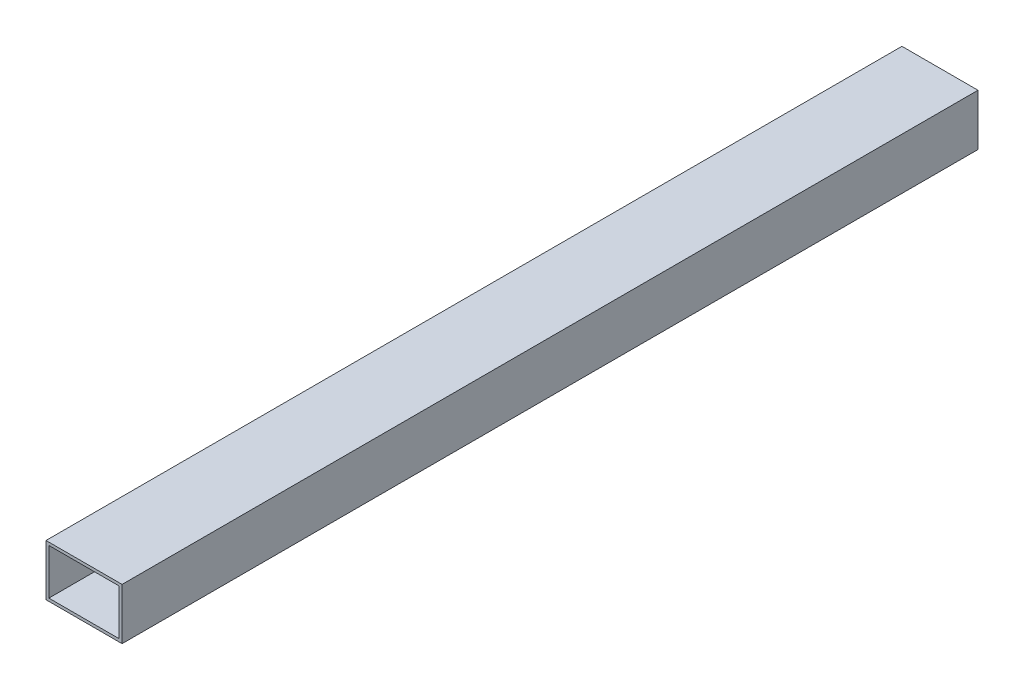
SolidWorks part; units mm, degrees
material "AISI 1020 Acier laminé à froid"
ref_plane "Plan de face" through (0, 0, 0) normal (0, 0, 1) x (1, 0, 0)
ref_plane "Plan de dessus" through (0, 0, 0) normal (0, 1, 0) x (1, 0, 0)
ref_plane "Plan de droite" through (0, 0, 0) normal (1, 0, 0) x (0, 0, -1)
sketch "Esquisse1" plane through (0, 0, 0) normal (0, 0, 1) x (1, 0, 0)
  line L1 (0, 0) -> (40, 0)
  line L2 (0, 0) -> (0, 27)
  line L3 (0, 27) -> (40, 27)
  line L4 (40, 0) -> (40, 27)
  line L5 (1.5, 25.5) -> (38.5, 25.5)
  line L6 (1.5, 25.5) -> (1.5, 1.5)
  line L7 (1.5, 1.5) -> (38.5, 1.5)
  line L8 (38.5, 25.5) -> (38.5, 1.5)
  dimension "D1" = 40
  dimension "D2" = 27
  dimension "D3" = 1.5
  dimension "D4" = 1.5
  dimension "D5" = 1.5
  dimension "D6" = 1.5
extrude "Boss.-Extru.1" add sketch "Esquisse1" along normal blind 450
sketch "Esquisse2" plane through (0, 0, 0) normal (0, 1, 0) x (1, 0, 0)
  line L0 (0, -450) -> (40, -410)
  line L1 (40, -450) -> (40, 0) construction
  line L2 (0, -450) -> (40, -450)
  line L3 (40, -450) -> (40, -410)
  dimension "D1" = 45
extrude "Enlèv. mat.-Extru.1" [suppressed] cut sketch "Esquisse2" along normal through all
sketch "Esquisse4" plane through (0, 0, 0) normal (0, 1, 0) x (1, 0, 0)
  line L0 (0, 0) -> (40, -40)
  line L1 (40, -450) -> (40, 0) construction
  line L2 (40, -40) -> (40, 0)
  line L3 (40, 0) -> (0, 0)
  dimension "D1" = 45
extrude "Enlèv. mat.-Extru.3" [suppressed] cut sketch "Esquisse4" along normal through all
